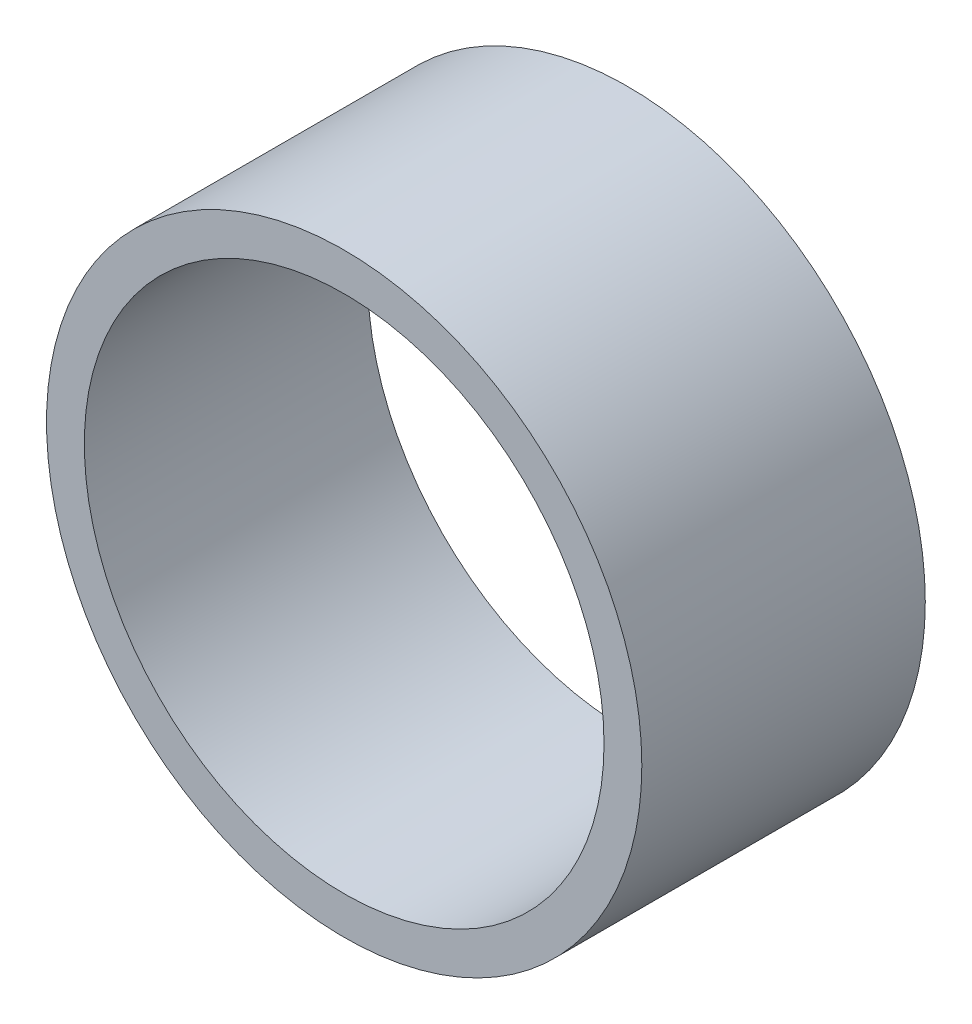
SolidWorks part; units mm, degrees
ref_plane "Front Plane" through (0, 0, 0) normal (0, 0, 1) x (1, 0, 0)
ref_plane "Top Plane" through (0, 0, 0) normal (0, 1, 0) x (1, 0, 0)
ref_plane "Right Plane" through (0, 0, 0) normal (1, 0, 0) x (0, 0, -1)
sketch "Sketch1" plane through (0, 0, 0) normal (0, 0, 1) x (1, 0, 0)
  circle A0 centre (0, 0) radius 2.75
  circle A1 centre (0, 0) radius 3.15
  dimension "D1" = 5.5
  dimension "D2" = 6.3
extrude "Boss-Extrude1" add sketch "Sketch1" along normal blind 3
